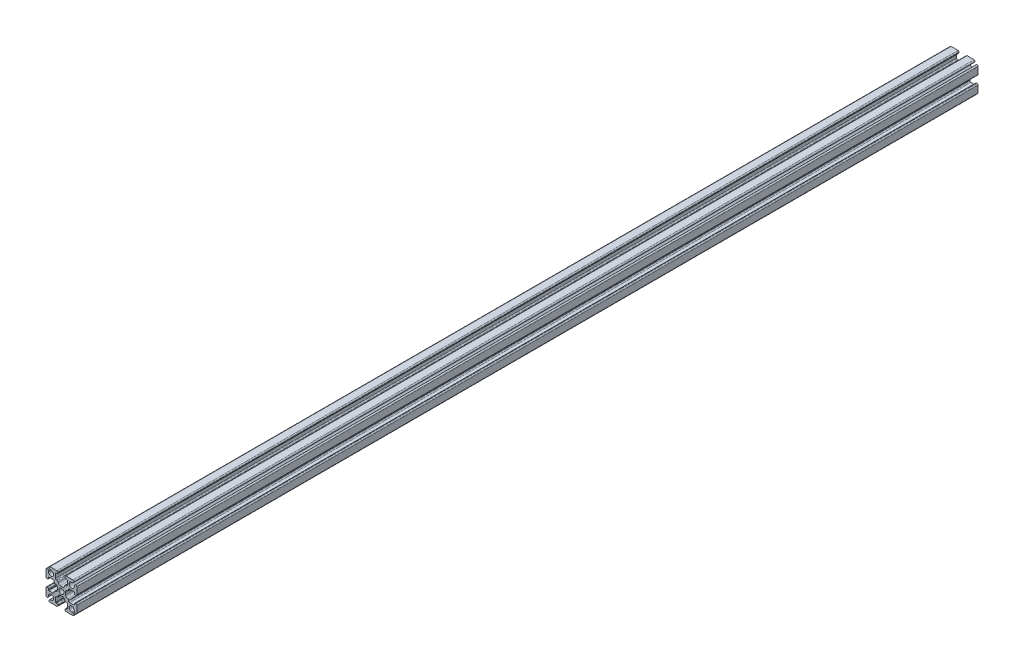
SolidWorks part; units mm, degrees
ref_plane "Front Plane" through (0, 0, 0) normal (0, 0, 1) x (1, 0, 0)
ref_plane "Top Plane" through (0, 0, 0) normal (0, 1, 0) x (1, 0, 0)
ref_plane "Right Plane" through (0, 0, 0) normal (1, 0, 0) x (0, 0, -1)
sketch "Sketch1" plane through (0, 0, 0) normal (0, 0, 1) x (1, 0, 0)
  line L0 (6.6464, 5.9393) -> (6.1636, 5.4565)
  line L1 (5.4565, 6.1636) -> (5.9393, 6.6464)
  line L2 (5.5858, 7.5) -> (2.25, 7.5)
  line L3 (1.75, 7) -> (1.75, 6.8)
  line L4 (2.25, 6.3) -> (2.65, 6.3)
  line L5 (2.85, 6.1) -> (2.85, 4)
  line L6 (2.35, 3.5) -> (2.1, 3.5)
  line L7 (0.6, 2) -> (-0.6, 2)
  line L8 (-2.1, 3.5) -> (-2.35, 3.5)
  line L9 (-2.85, 4) -> (-2.85, 6.1)
  line L10 (-2.65, 6.3) -> (-2.25, 6.3)
  line L11 (-1.75, 6.8) -> (-1.75, 7)
  line L12 (-2.25, 7.5) -> (-5.5858, 7.5)
  line L13 (-5.9393, 6.6464) -> (-5.4565, 6.1636)
  line L14 (-6.1636, 5.4565) -> (-6.6464, 5.9393)
  line L15 (-7.5, 5.5858) -> (-7.5, 2.25)
  line L16 (-7, 1.75) -> (-6.8, 1.75)
  line L17 (-6.3, 2.25) -> (-6.3, 2.65)
  line L18 (-6.1, 2.85) -> (-4, 2.85)
  line L19 (-3.5, 2.35) -> (-3.5, 2.1)
  line L20 (-2, 0.6) -> (-2, -0.6)
  line L21 (-3.5, -2.1) -> (-3.5, -2.35)
  line L22 (-4, -2.85) -> (-6.1, -2.85)
  line L23 (-6.3, -2.65) -> (-6.3, -2.25)
  line L24 (-6.8, -1.75) -> (-7, -1.75)
  line L25 (-7.5, -2.25) -> (-7.5, -5.5858)
  line L26 (-6.6464, -5.9393) -> (-6.1636, -5.4565)
  line L27 (-5.4565, -6.1636) -> (-5.9393, -6.6464)
  line L28 (-5.5858, -7.5) -> (-2.25, -7.5)
  line L29 (-1.75, -7) -> (-1.75, -6.8)
  line L30 (-2.25, -6.3) -> (-2.65, -6.3)
  line L31 (-2.85, -6.1) -> (-2.85, -4)
  line L32 (-2.35, -3.5) -> (-2.1, -3.5)
  line L33 (-0.6, -2) -> (0.6, -2)
  line L34 (2.1, -3.5) -> (2.35, -3.5)
  line L35 (2.85, -4) -> (2.85, -6.1)
  line L36 (2.65, -6.3) -> (2.25, -6.3)
  line L37 (1.75, -6.8) -> (1.75, -7)
  line L38 (2.25, -7.5) -> (5.5858, -7.5)
  line L39 (5.9393, -6.6464) -> (5.4565, -6.1636)
  line L40 (6.1636, -5.4565) -> (6.6464, -5.9393)
  line L41 (7.5, -5.5858) -> (7.5, -2.25)
  line L42 (7, -1.75) -> (6.8, -1.75)
  line L43 (6.3, -2.25) -> (6.3, -2.65)
  line L44 (6.1, -2.85) -> (4, -2.85)
  line L45 (3.5, -2.35) -> (3.5, -2.1)
  line L46 (2, -0.6) -> (2, 0.6)
  line L47 (3.5, 2.1) -> (3.5, 2.35)
  line L48 (4, 2.85) -> (6.1, 2.85)
  line L49 (6.3, 2.65) -> (6.3, 2.25)
  line L50 (6.8, 1.75) -> (7, 1.75)
  line L51 (7.5, 2.25) -> (7.5, 5.5858)
  circle A0 centre (0, 0) radius 1.25
  arc A1 (6.1636, 5.4565) -> (5.4565, 6.1636) centre (5, 5) cw
  arc A2 (5.9393, 6.6464) -> (5.5858, 7.5) centre (5.5858, 7) ccw
  arc A3 (2.25, 7.5) -> (1.75, 7) centre (2.25, 7) ccw
  arc A4 (1.75, 6.8) -> (2.25, 6.3) centre (2.25, 6.8) ccw
  arc A5 (2.65, 6.3) -> (2.85, 6.1) centre (2.65, 6.1) cw
  arc A6 (2.85, 4) -> (2.35, 3.5) centre (2.35, 4) cw
  arc A7 (2.1, 3.5) -> (1.6, 3) centre (2.1, 3) ccw
  arc A8 (1.6, 3) -> (0.6, 2) centre (0.6, 3) cw
  arc A9 (-0.6, 2) -> (-1.6, 3) centre (-0.6, 3) cw
  arc A10 (-1.6, 3) -> (-2.1, 3.5) centre (-2.1, 3) ccw
  arc A11 (-2.35, 3.5) -> (-2.85, 4) centre (-2.35, 4) cw
  arc A12 (-2.85, 6.1) -> (-2.65, 6.3) centre (-2.65, 6.1) cw
  arc A13 (-2.25, 6.3) -> (-1.75, 6.8) centre (-2.25, 6.8) ccw
  arc A14 (-1.75, 7) -> (-2.25, 7.5) centre (-2.25, 7) ccw
  arc A15 (-5.5858, 7.5) -> (-5.9393, 6.6464) centre (-5.5858, 7) ccw
  arc A16 (-5.4565, 6.1636) -> (-6.1636, 5.4565) centre (-5, 5) cw
  arc A17 (-6.6464, 5.9393) -> (-7.5, 5.5858) centre (-7, 5.5858) ccw
  arc A18 (-7.5, 2.25) -> (-7, 1.75) centre (-7, 2.25) ccw
  arc A19 (-6.8, 1.75) -> (-6.3, 2.25) centre (-6.8, 2.25) ccw
  arc A20 (-6.3, 2.65) -> (-6.1, 2.85) centre (-6.1, 2.65) cw
  arc A21 (-4, 2.85) -> (-3.5, 2.35) centre (-4, 2.35) cw
  arc A22 (-3.5, 2.1) -> (-3, 1.6) centre (-3, 2.1) ccw
  arc A23 (-3, 1.6) -> (-2, 0.6) centre (-3, 0.6) cw
  arc A24 (-2, -0.6) -> (-3, -1.6) centre (-3, -0.6) cw
  arc A25 (-3, -1.6) -> (-3.5, -2.1) centre (-3, -2.1) ccw
  arc A26 (-3.5, -2.35) -> (-4, -2.85) centre (-4, -2.35) cw
  arc A27 (-6.1, -2.85) -> (-6.3, -2.65) centre (-6.1, -2.65) cw
  arc A28 (-6.3, -2.25) -> (-6.8, -1.75) centre (-6.8, -2.25) ccw
  arc A29 (-7, -1.75) -> (-7.5, -2.25) centre (-7, -2.25) ccw
  arc A30 (-7.5, -5.5858) -> (-6.6464, -5.9393) centre (-7, -5.5858) ccw
  arc A31 (-6.1636, -5.4565) -> (-5.4565, -6.1636) centre (-5, -5) cw
  arc A32 (-5.9393, -6.6464) -> (-5.5858, -7.5) centre (-5.5858, -7) ccw
  arc A33 (-2.25, -7.5) -> (-1.75, -7) centre (-2.25, -7) ccw
  arc A34 (-1.75, -6.8) -> (-2.25, -6.3) centre (-2.25, -6.8) ccw
  arc A35 (-2.65, -6.3) -> (-2.85, -6.1) centre (-2.65, -6.1) cw
  arc A36 (-2.85, -4) -> (-2.35, -3.5) centre (-2.35, -4) cw
  arc A37 (-2.1, -3.5) -> (-1.6, -3) centre (-2.1, -3) ccw
  arc A38 (-1.6, -3) -> (-0.6, -2) centre (-0.6, -3) cw
  arc A39 (0.6, -2) -> (1.6, -3) centre (0.6, -3) cw
  arc A40 (1.6, -3) -> (2.1, -3.5) centre (2.1, -3) ccw
  arc A41 (2.35, -3.5) -> (2.85, -4) centre (2.35, -4) cw
  arc A42 (2.85, -6.1) -> (2.65, -6.3) centre (2.65, -6.1) cw
  arc A43 (2.25, -6.3) -> (1.75, -6.8) centre (2.25, -6.8) ccw
  arc A44 (1.75, -7) -> (2.25, -7.5) centre (2.25, -7) ccw
  arc A45 (5.5858, -7.5) -> (5.9393, -6.6464) centre (5.5858, -7) ccw
  arc A46 (5.4565, -6.1636) -> (6.1636, -5.4565) centre (5, -5) cw
  arc A47 (6.6464, -5.9393) -> (7.5, -5.5858) centre (7, -5.5858) ccw
  arc A48 (7.5, -2.25) -> (7, -1.75) centre (7, -2.25) ccw
  arc A49 (6.8, -1.75) -> (6.3, -2.25) centre (6.8, -2.25) ccw
  arc A50 (6.3, -2.65) -> (6.1, -2.85) centre (6.1, -2.65) cw
  arc A51 (4, -2.85) -> (3.5, -2.35) centre (4, -2.35) cw
  arc A52 (3.5, -2.1) -> (3, -1.6) centre (3, -2.1) ccw
  arc A53 (3, -1.6) -> (2, -0.6) centre (3, -0.6) cw
  arc A54 (2, 0.6) -> (3, 1.6) centre (3, 0.6) cw
  arc A55 (3, 1.6) -> (3.5, 2.1) centre (3, 2.1) ccw
  arc A56 (3.5, 2.35) -> (4, 2.85) centre (4, 2.35) cw
  arc A57 (6.1, 2.85) -> (6.3, 2.65) centre (6.1, 2.65) cw
  arc A58 (6.3, 2.25) -> (6.8, 1.75) centre (6.8, 2.25) ccw
  arc A59 (7, 1.75) -> (7.5, 2.25) centre (7, 2.25) ccw
  arc A60 (7.5, 5.5858) -> (6.6464, 5.9393) centre (7, 5.5858) ccw
extrude "Boss-Extrude1" add sketch "Sketch1" along normal blind 438.15
